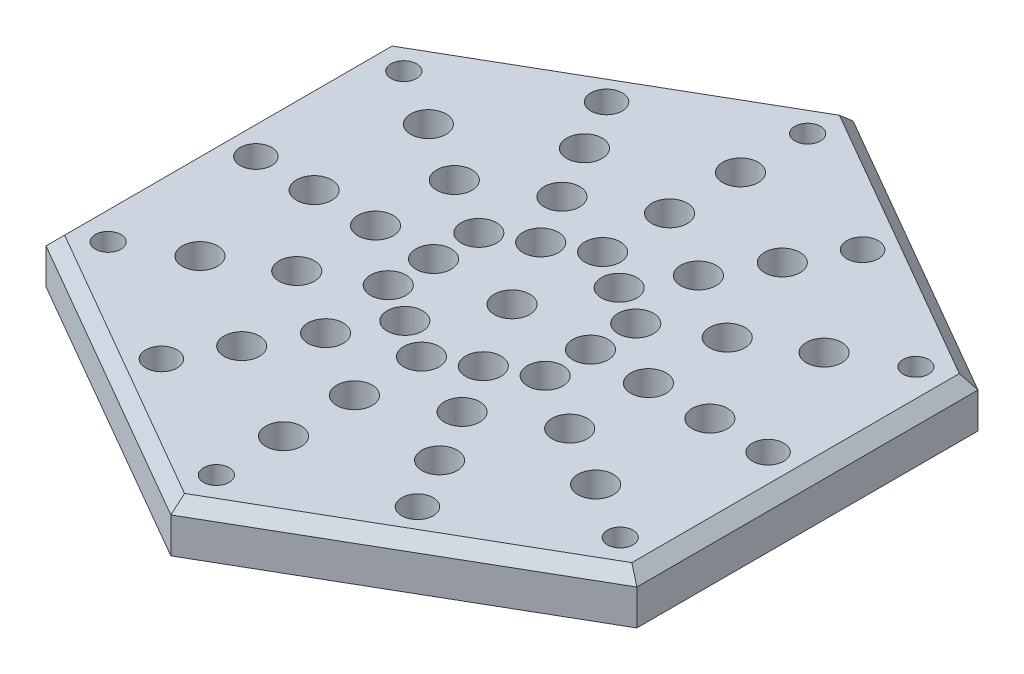
SolidWorks part; units mm, degrees
ref_plane "前基準面" through (0, 0, 0) normal (0, 0, 1) x (1, 0, 0)
ref_plane "上基準面" through (0, 0, 0) normal (0, 1, 0) x (1, 0, 0)
ref_plane "右基準面" through (0, 0, 0) normal (1, 0, 0) x (0, 0, -1)
sketch "草圖2" plane through (0, 0, 0) normal (0, 1, 0) x (1, 0, 0)
  line L1 (0, 86.6025) -> (-75, 43.3013)
  line L2 (-75, 43.3013) -> (-75, -43.3013)
  line L3 (-75, -43.3013) -> (0, -86.6025)
  line L4 (0, -86.6025) -> (75, -43.3013)
  line L5 (75, -43.3013) -> (75, 43.3013)
  line L6 (75, 43.3013) -> (0, 86.6025)
  circle A0 centre (0, 0) radius 75 construction
  dimension "D1" = 150
extrude "填料-伸長2" add sketch "草圖2" along normal blind 12
chamfer "導角1" distance 3 angle 45 6 edges at (75, 12, 0) (37.5, 12, 64.9519) (-37.5, 12, 64.9519) (-75, 12, 0) (-37.5, 12, -64.9519) (37.5, 12, -64.9519)
sketch "草圖3" plane through (0, 12, 0) normal (0, 1, 0) x (1, 0, 0)
  line L0 (-65, 0) -> (65, 0)
  line L1 (-32.5, -56.5) -> (32.5, -56.5)
  line L2 (-32.5, -56.5) -> (-32.5, 56.5)
  line L3 (-32.5, 56.5) -> (32.5, 56.5)
  line L4 (32.5, -56.5) -> (32.5, 56.5)
  line L5 (-32.5, -56.5) -> (32.5, 56.5) construction
  line L6 (-32.5, 56.5) -> (32.5, -56.5) construction
  line L7 (0, 75.0555) -> (-65, 37.5278)
  line L8 (-65, 37.5278) -> (-65, -37.5278)
  line L9 (-65, -37.5278) -> (0, -75.0555)
  line L10 (0, -75.0555) -> (65, -37.5278)
  line L11 (65, -37.5278) -> (65, 37.5278)
  line L12 (65, 37.5278) -> (0, 75.0555)
  circle A0 centre (0, 0) radius 65 construction
  point P0 (0, 0)
  dimension "D1" = 130
  dimension "D2" = 65
  dimension "D3" = 113
  dimension "D4" = 75.0555
hole_wizard "Ø6.0mm 定位孔1" positions "3D草圖2" profile "草圖7" hole size "Ø6.0" standard "ISO" end condition through all
sketch3d "3D草圖2"
  point P0 (-65, 12, 37.5278)
  point P3 (-65, 12, -37.5278)
  point P6 (0, 12, -75.0555)
  point P9 (65, 12, -37.5278)
  point P15 (0, 12, 75.0555)
  point P19 (65, 12, 37.5278)
  point P23 (0, 0, 0)
sketch "草圖7" plane through (-65, 12, 37.5278) normal (1, 0, 0) x (0, 0, 1)
  line L0 (0, 0) -> (0, 12)
  line L1 (0, 12) -> (3.25, 12)
  line L2 (3.25, 12) -> (3.25, 0)
  line L5 (3.25, 0) -> (0, 0)
  line L11 (0, -6.35) -> (0, 107.95) construction
  dimension "砮 ふ 畖" = 6.5
  dimension "砮 ふ瞏 " = 12
hole_wizard "Ø8.0mm 定位孔1" positions "3D草圖3" profile "草圖9" hole size "Ø8.0" standard "ISO" end condition through all
sketch3d "3D草圖3"
  point P0 (-65, 12, 0)
  point P3 (-32.5, 12, 56.5)
  point P6 (32.5, 12, 56.5)
  point P9 (32.5, 12, -56.5)
  point P12 (-32.5, 12, -56.5)
  point P15 (65, 12, 0)
sketch "草圖9" plane through (-65, 12, 0) normal (1, 0, 0) x (0, 0, 1)
  line L0 (0, 0) -> (0, 12)
  line L1 (0, 12) -> (4, 12)
  line L2 (4, 12) -> (4, 0)
  line L5 (4, 0) -> (0, 0)
  line L11 (0, -6.35) -> (0, 107.95) construction
  dimension "砮 ふ 畖" = 8
  dimension "砮 ふ瞏 " = 12
sketch "草圖10" plane through (0, 12, 0) normal (0, 1, 0) x (1, 0, 0)
  line L1 (0, 58) -> (-50.2295, 29)
  line L2 (-50.2295, 29) -> (-50.2295, -29)
  line L3 (-50.2295, -29) -> (0, -58)
  line L4 (0, -58) -> (50.2295, -29)
  line L5 (50.2295, -29) -> (50.2295, 29)
  line L6 (50.2295, 29) -> (0, 58)
  line L7 (-25.1147, 43.5) -> (-50.2295, 0)
  line L8 (-50.2295, 0) -> (-25.1147, -43.5)
  line L9 (-25.1147, -43.5) -> (25.1147, -43.5)
  line L10 (25.1147, -43.5) -> (50.2295, 0)
  line L11 (50.2295, 0) -> (25.1147, 43.5)
  line L12 (25.1147, 43.5) -> (-25.1147, 43.5)
  line L13 (0, 40) -> (-34.641, 20)
  line L14 (-34.641, 20) -> (-34.641, -20)
  line L15 (-34.641, -20) -> (0, -40)
  line L16 (0, -40) -> (34.641, -20)
  line L17 (34.641, -20) -> (34.641, 20)
  line L18 (34.641, 20) -> (0, 40)
  line L19 (-17.3205, 30) -> (-34.641, 0)
  line L20 (-34.641, 0) -> (-17.3205, -30)
  line L21 (-17.3205, -30) -> (17.3205, -30)
  line L22 (17.3205, -30) -> (34.641, 0)
  line L23 (34.641, 0) -> (17.3205, 30)
  line L24 (17.3205, 30) -> (-17.3205, 30)
  line L25 (0, 23) -> (-19.9186, 11.5)
  line L26 (-19.9186, 11.5) -> (-19.9186, -11.5)
  line L27 (-19.9186, -11.5) -> (0, -23)
  line L28 (0, -23) -> (19.9186, -11.5)
  line L29 (19.9186, -11.5) -> (19.9186, 11.5)
  line L30 (19.9186, 11.5) -> (0, 23)
  line L31 (-9.9593, 17.25) -> (-19.9186, 0)
  line L32 (-19.9186, 0) -> (-9.9593, -17.25)
  line L33 (-9.9593, -17.25) -> (9.9593, -17.25)
  line L34 (9.9593, -17.25) -> (19.9186, 0)
  line L35 (19.9186, 0) -> (9.9593, 17.25)
  line L36 (9.9593, 17.25) -> (-9.9593, 17.25)
  circle A0 centre (0, 0) radius 50.2295 construction
  circle A1 centre (0, 0) radius 43.5 construction
  circle A2 centre (0, 0) radius 34.641 construction
  circle A3 centre (0, 0) radius 30 construction
  circle A4 centre (0, 0) radius 19.9186 construction
  circle A5 centre (0, 0) radius 17.25 construction
  point P50 (0, 0)
  dimension "D1" = 58
  dimension "D2" = 40
  dimension "D3" = 23
hole_wizard "Ø6.0mm 定位孔2" positions "3D草圖4" profile "草圖11" hole size "Ø6.0" standard "ISO"
sketch3d "3D草圖4"
  line L0 (50.2295, 12, -29) -> (0, 12, -58) construction
  point P0 (-50.2295, 12, -29)
  point P3 (-25.1147, 12, -43.5)
  point P6 (0, 12, -58)
  point P9 (25.1147, 12, -43.5)
  point P13 (50.2295, 12, -29)
  point P16 (50.2295, 12, 0)
  point P19 (25.1147, 12, 43.5)
  point P22 (0, 12, 58)
  point P25 (-25.1147, 12, 43.5)
  point P28 (-50.2295, 12, 29)
  point P31 (-50.2295, 12, 0)
  point P34 (0, 12, -40)
  point P37 (34.641, 12, -20)
  point P40 (17.3205, 12, -30)
  point P43 (-17.3205, 12, -30)
  point P46 (-34.641, 12, -20)
  point P49 (-19.9186, 12, -11.5)
  point P52 (-9.9593, 12, -17.25)
  point P55 (0, 0, 0)
  point P58 (0, 12, -23)
  point P61 (9.9593, 12, -17.25)
  point P64 (19.9186, 12, -11.5)
  point P67 (19.9186, 12, 0)
  point P70 (9.9593, 12, 17.25)
  point P73 (0, 12, 23)
  point P76 (-9.9593, 12, 17.25)
  point P79 (-19.9186, 12, 11.5)
  point P82 (-34.641, 12, 20)
  point P85 (-34.641, 12, 0)
  point P88 (-17.3205, 12, 30)
  point P91 (0, 12, 40)
  point P94 (17.3205, 12, 30)
  point P97 (34.641, 12, 20)
  point P100 (34.641, 12, 0)
  point P103 (0, 12, 0)
  point P106 (25.1147, 12, -43.5)
sketch "草圖11" plane through (-50.2295, 12, -29) normal (1, 0, 0) x (0, 0, 1)
  line L0 (0, 0) -> (0, 12)
  line L1 (0, 12) -> (4.5, 12)
  line L2 (4.5, 12) -> (4.5, 0)
  line L5 (4.5, 0) -> (0, 0)
  line L11 (0, -6.35) -> (0, 107.95) construction
  dimension "砮 ふ 畖" = 9
  dimension "砮 ふ瞏 " = 12
hole_wizard "Ø6.0mm 定位孔3" positions "3D草圖5" profile "草圖12" hole size "Ø6.0" standard "ISO" end condition through all
sketch3d "3D草圖5"
  point P0 (25.1147, 12, -43.5)
  point P3 (50.2295, 12, 29)
  point P7 (19.9186, 12, 11.5)
  point P10 (-19.9186, 12, 0)
sketch "草圖12" plane through (25.1147, 12, -43.5) normal (1, 0, 0) x (0, 0, 1)
  line L0 (0, 0) -> (0, 12)
  line L1 (0, 12) -> (4.5, 12)
  line L2 (4.5, 12) -> (4.5, 0)
  line L5 (4.5, 0) -> (0, 0)
  line L11 (0, -6.35) -> (0, 107.95) construction
  dimension "砮 ふ 畖" = 9
  dimension "砮 ふ瞏 " = 12
